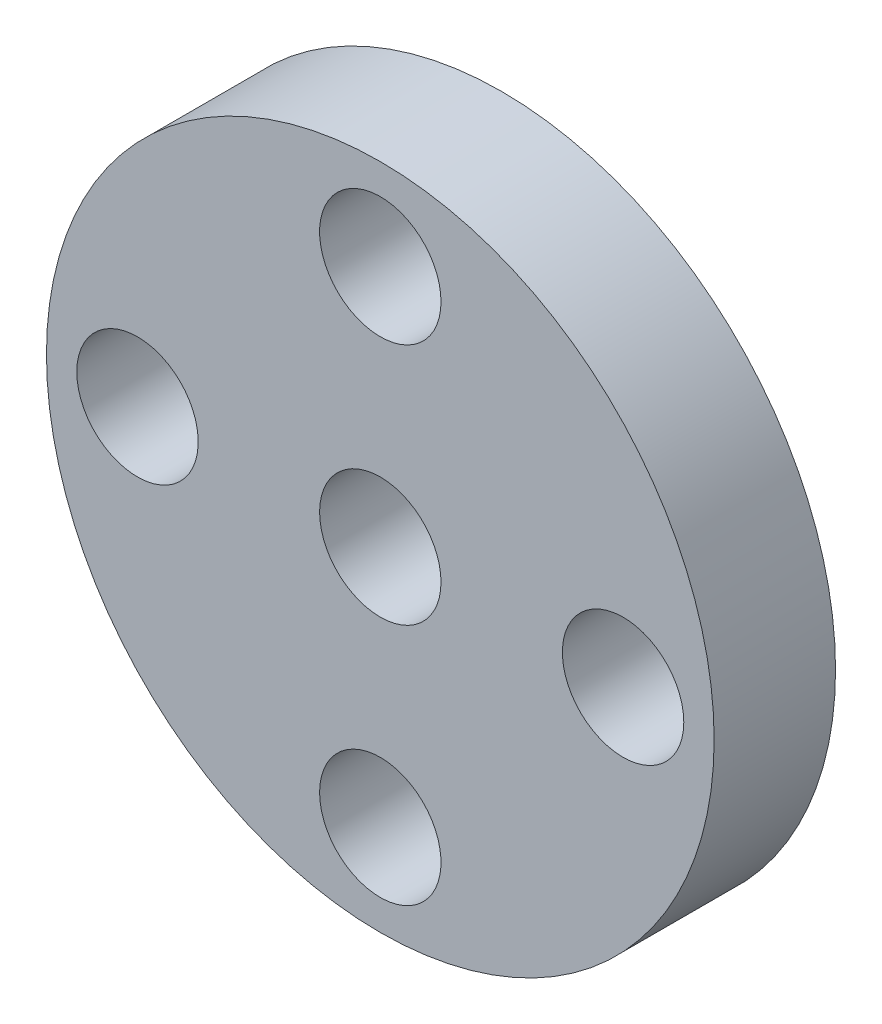
SolidWorks part; units mm, degrees
ref_plane "Ön Düzlem" through (0, 0, 0) normal (0, 0, 1) x (1, 0, 0)
ref_plane "Üst Düzlem" through (0, 0, 0) normal (0, 1, 0) x (1, 0, 0)
ref_plane "Sağ Düzlem" through (0, 0, 0) normal (1, 0, 0) x (0, 0, -1)
sketch "Çizim1" plane through (0, 0, 0) normal (0, 0, 1) x (1, 0, 0)
  circle A0 centre (0, 0) radius 11
  circle A1 centre (0, 0) radius 2
  circle A2 centre (8, 0) radius 2
  circle A3 centre (0, 8) radius 2
  circle A4 centre (-8, 0) radius 2
  circle A5 centre (0, -8) radius 2
  dimension "D1" = 22
  dimension "D2" = 4
  dimension "D3" = 4
  dimension "D4" = 8
  dimension "D5" = 4
  dimension "D6" = 8
  dimension "D7" = 8
  dimension "D8" = 8
extrude "Yükseklik-Ekstrüzyon1" add sketch "Çizim1" along normal blind 4
sketch "Çizim2" plane through (0, 0, 0) normal (0, 0, -1) x (-1, 0, 0)
  circle A0 centre (0, 0) radius 2
  circle A1 centre (0, 0) radius 4
  dimension "D1" = 8
extrude "Yükseklik-Ekstrüzyon2" add sketch "Çizim2" along normal blind 4
